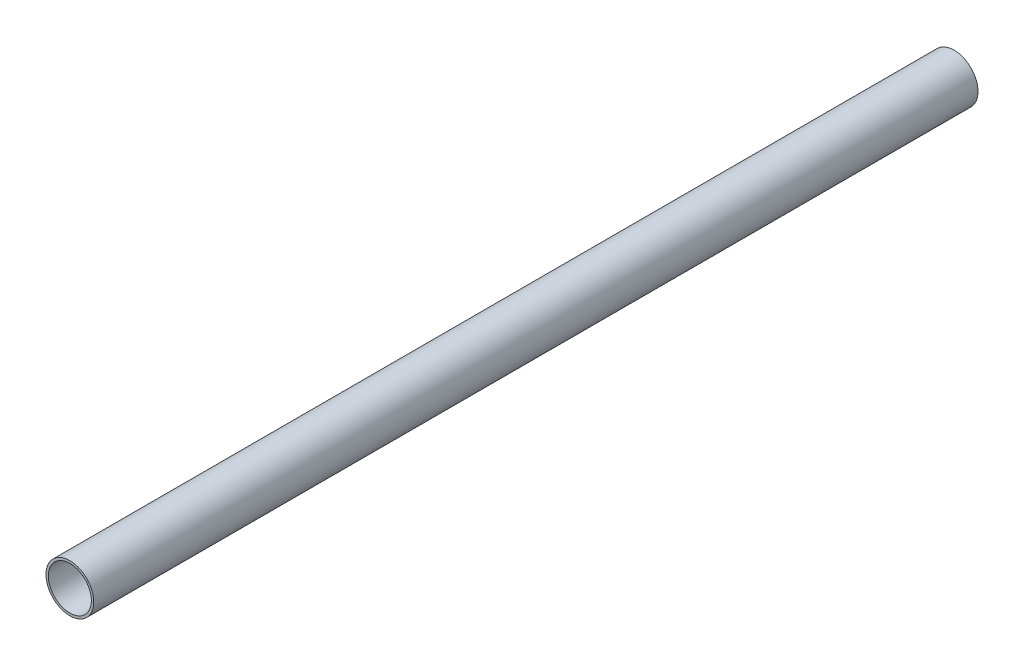
SolidWorks part; units mm, degrees
ref_plane "Front Plane" through (0, 0, 0) normal (0, 0, 1) x (1, 0, 0)
ref_plane "Top Plane" through (0, 0, 0) normal (0, 1, 0) x (1, 0, 0)
ref_plane "Right Plane" through (0, 0, 0) normal (1, 0, 0) x (0, 0, -1)
sketch "Sketch1" plane through (0, 0, 0) normal (0, 0, 1) x (1, 0, 0)
  circle A0 centre (0, 0) radius 10
  circle A1 centre (0, 0) radius 9
extrude "Boss-Extrude1" add sketch "Sketch1" along normal blind 370
